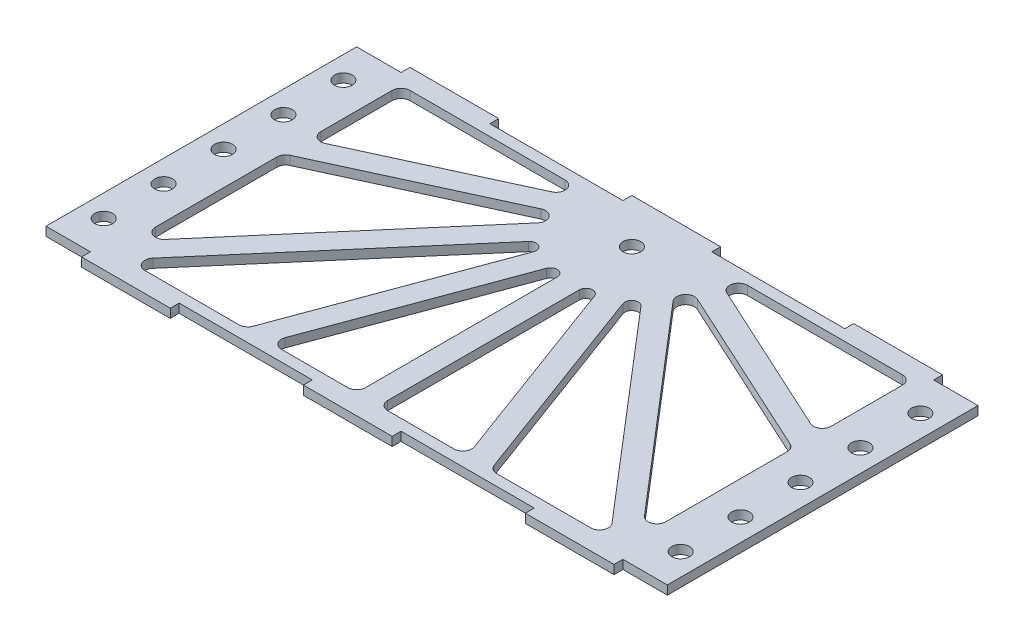
SolidWorks part; units mm, degrees
material "AISI 4340 Steel, normalized"
ref_plane "Front Plane" through (0, 0, 0) normal (0, 0, 1) x (1, 0, 0)
ref_plane "Top Plane" through (0, 0, 0) normal (0, 1, 0) x (1, 0, 0)
ref_plane "Right Plane" through (0, 0, 0) normal (1, 0, 0) x (0, 0, -1)
sketch "Sketch1" plane through (0, 0, 0) normal (0, 1, 0) x (1, 0, 0)
  line B0 (-34.9462, -16.0725) -> (34.9462, 16.0725)
  line B1 (-65.6176, 32.7066) -> (-65.6176, -115.2934)
  line B2 (-65.6176, -115.2934) -> (214.3824, -115.2934)
  line B3 (214.3824, -115.2934) -> (214.3824, 32.7066)
  line B4 (-40.6176, 19.7066) -> (-40.6176, -12.4384)
  line B5 (33.2748, 23.7066) -> (-36.6176, 23.7066)
  line B6 (-40.6176, -32.2509) -> (-40.6176, -86.9641)
  line B7 (39.1267, 6.9883) -> (-38.289, -28.6169)
  line B8 (-33.5806, -89.5673) -> (43.8351, 0.751)
  line B9 (-26.0496, -106.2934) -> (16.328, -106.2934)
  line B10 (20.0796, -103.6812) -> (54.1909, -11.4664)
  line B11 (49.0994, -8.4732) -> (-29.0866, -99.6903)
  line B12 (35.52, -106.2934) -> (65.3824, -106.2934)
  line B13 (63.5687, -14.9385) -> (31.7685, -100.9057)
  line B14 (69.3824, -102.2934) -> (69.3824, -15.9793)
  line B15 (83.3824, -106.2934) -> (113.2448, -106.2934)
  line B16 (79.3824, -15.9793) -> (79.3824, -102.2934)
  line B17 (116.9963, -100.9057) -> (85.1961, -14.9385)
  line B18 (189.3824, -12.4384) -> (189.3824, 19.7066)
  line B19 (113.8186, 16.0725) -> (183.711, -16.0725)
  line B20 (185.3824, 23.7066) -> (115.49, 23.7066)
  line B21 (187.0538, -28.6169) -> (109.6381, 6.9883)
  line B22 (189.3824, -86.9641) -> (189.3824, -32.2509)
  line B23 (104.9297, 0.751) -> (182.3454, -89.5673)
  line B24 (132.4368, -106.2934) -> (174.8144, -106.2934)
  line B25 (94.5739, -11.4664) -> (128.6852, -103.6812)
  line B26 (177.8514, -99.6903) -> (99.6654, -8.4732)
  line B27 (-65.6176, 32.7066) -> (214.3824, 32.7066)
  circle B28 centre (74.3824, 12.7066) radius 4
  circle B29 centre (204.3824, 12.7066) radius 4
  circle B30 centre (204.3824, -14.2934) radius 4
  circle B31 centre (204.3824, -41.2934) radius 4
  circle B32 centre (204.3824, -68.2934) radius 4
  circle B33 centre (204.3824, -95.2934) radius 4
  circle B34 centre (-55.6176, -95.2934) radius 4
  circle B35 centre (-55.6176, -68.2934) radius 4
  circle B36 centre (-55.6176, -41.2934) radius 4
  circle B37 centre (-55.6176, -14.2934) radius 4
  circle B38 centre (-55.6176, 12.7066) radius 4
  arc B39 (34.9462, 16.0725) -> (33.2748, 23.7066) centre (33.2748, 19.7066) ccw
  arc B40 (-40.6176, -12.4384) -> (-34.9462, -16.0725) centre (-36.6176, -12.4384) ccw
  arc B41 (-36.6176, 23.7066) -> (-40.6176, 19.7066) centre (-36.6176, 19.7066) ccw
  arc B42 (-40.6176, -86.9641) -> (-33.5806, -89.5673) centre (-36.6176, -86.9641) ccw
  arc B43 (43.8351, 0.751) -> (39.1267, 6.9883) centre (40.7981, 3.3542) ccw
  arc B44 (-29.0866, -99.6903) -> (-26.0496, -106.2934) centre (-26.0496, -102.2934) ccw
  arc B45 (16.328, -106.2934) -> (20.0796, -103.6812) centre (16.328, -102.2934) ccw
  arc B46 (54.1909, -11.4664) -> (49.0994, -8.4732) centre (51.3772, -10.4256) ccw
  arc B47 (65.3824, -106.2934) -> (69.3824, -102.2934) centre (65.3824, -102.2934) ccw
  arc B48 (31.7685, -100.9057) -> (35.52, -106.2934) centre (35.52, -102.2934) ccw
  arc B49 (69.3824, -15.9793) -> (63.5687, -14.9385) centre (66.3824, -15.9793) ccw
  arc B50 (113.2448, -106.2934) -> (116.9963, -100.9057) centre (113.2448, -102.2934) ccw
  arc B51 (79.3824, -102.2934) -> (83.3824, -106.2934) centre (83.3824, -102.2934) ccw
  arc B52 (85.1961, -14.9385) -> (79.3824, -15.9793) centre (82.3824, -15.9793) ccw
  arc B53 (183.711, -16.0725) -> (189.3824, -12.4384) centre (185.3824, -12.4384) ccw
  arc B54 (189.3824, 19.7066) -> (185.3824, 23.7066) centre (185.3824, 19.7066) ccw
  arc B55 (115.49, 23.7066) -> (113.8186, 16.0725) centre (115.49, 19.7066) ccw
  arc B56 (109.6381, 6.9883) -> (104.9297, 0.751) centre (107.9667, 3.3542) ccw
  arc B57 (189.3824, -32.2509) -> (187.0538, -28.6169) centre (185.3824, -32.2509) ccw
  arc B58 (182.3454, -89.5673) -> (189.3824, -86.9641) centre (185.3824, -86.9641) ccw
  arc B59 (174.8144, -106.2934) -> (177.8514, -99.6903) centre (174.8144, -102.2934) ccw
  arc B60 (128.6852, -103.6812) -> (132.4368, -106.2934) centre (132.4368, -102.2934) ccw
  arc B61 (99.6654, -8.4732) -> (94.5739, -11.4664) centre (97.3876, -10.4256) ccw
sketch_block_instance "Block-pedalbox bottom-1"
sketch_block "Block-pedalbox bottom"
sketch "Sketch2" plane through (0, 0, 0) normal (0, 1, 0) x (1, 0, 0)
  line L0 (39.1267, 6.9883) -> (-38.289, -28.6169) construction
  line L1 (-33.5806, -89.5673) -> (43.8351, 0.751) construction
  line L2 (-40.6176, -32.2509) -> (-40.6176, -86.9641) construction
  line L3 (-65.6176, 32.7066) -> (-65.6176, -115.2934) construction
  line L4 (-65.6176, -115.2934) -> (214.3824, -115.2934) construction
  line L5 (214.3824, -115.2934) -> (214.3824, 32.7066) construction
  line L6 (-65.6176, 32.7066) -> (214.3824, 32.7066) construction
  line L7 (-40.6176, 19.7066) -> (-40.6176, -12.4384) construction
  line L8 (-34.9462, -16.0725) -> (34.9462, 16.0725) construction
  line L9 (33.2748, 23.7066) -> (-36.6176, 23.7066) construction
  line L10 (-26.0496, -106.2934) -> (16.328, -106.2934) construction
  line L11 (49.0994, -8.4732) -> (-29.0866, -99.6903) construction
  line L12 (20.0796, -103.6812) -> (54.1909, -11.4664) construction
  line L13 (79.3824, -15.9793) -> (79.3824, -102.2934) construction
  line L14 (83.3824, -106.2934) -> (113.2448, -106.2934) construction
  line L15 (116.9963, -100.9057) -> (85.1961, -14.9385) construction
  line L16 (35.52, -106.2934) -> (65.3824, -106.2934) construction
  line L17 (69.3824, -102.2934) -> (69.3824, -15.9793) construction
  line L18 (63.5687, -14.9385) -> (31.7685, -100.9057) construction
  line L19 (187.0538, -28.6169) -> (109.6381, 6.9883) construction
  line L20 (104.9297, 0.751) -> (182.3454, -89.5673) construction
  line L21 (189.3824, -86.9641) -> (189.3824, -32.2509) construction
  line L22 (185.3824, 23.7066) -> (115.49, 23.7066) construction
  line L23 (189.3824, -12.4384) -> (189.3824, 19.7066) construction
  line L24 (113.8186, 16.0725) -> (183.711, -16.0725) construction
  line L25 (94.5739, -11.4664) -> (128.6852, -103.6812) construction
  line L26 (132.4368, -106.2934) -> (174.8144, -106.2934) construction
  line L27 (177.8514, -99.6903) -> (99.6654, -8.4732) construction
  line L28 (39.1267, 6.9883) -> (-38.289, -28.6169)
  line L29 (-33.5806, -89.5673) -> (43.8351, 0.751)
  line L30 (-40.6176, -32.2509) -> (-40.6176, -86.9641)
  line L31 (-65.6176, 28.7066) -> (-65.6176, -111.2934)
  line L32 (-45.6176, -115.2934) -> (-5.6176, -115.2934)
  line L33 (214.3824, -111.2934) -> (214.3824, 28.7066)
  line L34 (-45.6176, 32.7066) -> (-5.6176, 32.7066)
  line L35 (-40.6176, 19.7066) -> (-40.6176, -12.4384)
  line L36 (-34.9462, -16.0725) -> (34.9462, 16.0725)
  line L37 (33.2748, 23.7066) -> (-36.6176, 23.7066)
  line L38 (-26.0496, -106.2934) -> (16.328, -106.2934)
  line L39 (49.0994, -8.4732) -> (-29.0866, -99.6903)
  line L40 (20.0796, -103.6812) -> (54.1909, -11.4664)
  line L41 (79.3824, -15.9793) -> (79.3824, -102.2934)
  line L42 (83.3824, -106.2934) -> (113.2448, -106.2934)
  line L43 (116.9963, -100.9057) -> (85.1961, -14.9385)
  line L44 (35.52, -106.2934) -> (65.3824, -106.2934)
  line L45 (69.3824, -102.2934) -> (69.3824, -15.9793)
  line L46 (63.5687, -14.9385) -> (31.7685, -100.9057)
  line L47 (187.0538, -28.6169) -> (109.6381, 6.9883)
  line L48 (104.9297, 0.751) -> (182.3454, -89.5673)
  line L49 (189.3824, -86.9641) -> (189.3824, -32.2509)
  line L50 (185.3824, 23.7066) -> (115.49, 23.7066)
  line L51 (189.3824, -12.4384) -> (189.3824, 19.7066)
  line L52 (113.8186, 16.0725) -> (183.711, -16.0725)
  line L53 (94.5739, -11.4664) -> (128.6852, -103.6812)
  line L54 (132.4368, -106.2934) -> (174.8144, -106.2934)
  line L55 (177.8514, -99.6903) -> (99.6654, -8.4732)
  line L56 (74.3824, 28.7066) -> (74.3824, -115.2934) construction
  line L57 (-65.6176, 28.7066) -> (-45.6176, 28.7066)
  line L58 (54.3824, 28.7066) -> (54.3824, 32.7066)
  line L59 (-5.6176, 28.7066) -> (-5.6176, 32.7066)
  line L60 (-45.6176, 28.7066) -> (-45.6176, 32.7066)
  line L61 (94.3824, 28.7066) -> (94.3824, 32.7066)
  line L62 (154.3824, 28.7066) -> (154.3824, 32.7066)
  line L63 (194.3824, 28.7066) -> (194.3824, 32.7066)
  line L64 (-65.6176, -41.2934) -> (74.3824, -41.2934) construction
  line L65 (194.3824, -111.2934) -> (194.3824, -115.2934)
  line L66 (154.3824, -111.2934) -> (154.3824, -115.2934)
  line L67 (94.3824, -111.2934) -> (94.3824, -115.2934)
  line L68 (54.3824, -111.2934) -> (54.3824, -115.2934)
  line L69 (-5.6176, -111.2934) -> (-5.6176, -115.2934)
  line L70 (-65.6176, -111.2934) -> (-45.6176, -111.2934)
  line L71 (-45.6176, -111.2934) -> (-45.6176, -115.2934)
  line L72 (54.3824, 32.7066) -> (94.3824, 32.7066)
  line L73 (154.3824, 32.7066) -> (194.3824, 32.7066)
  line L74 (-5.6176, 28.7066) -> (54.3824, 28.7066)
  line L75 (94.3824, 28.7066) -> (154.3824, 28.7066)
  line L76 (194.3824, 28.7066) -> (214.3824, 28.7066)
  line L77 (-5.6176, -111.2934) -> (54.3824, -111.2934)
  line L78 (54.3824, -115.2934) -> (94.3824, -115.2934)
  line L79 (94.3824, -111.2934) -> (154.3824, -111.2934)
  line L80 (154.3824, -115.2934) -> (194.3824, -115.2934)
  line L81 (194.3824, -111.2934) -> (214.3824, -111.2934)
  arc A0 (43.8351, 0.751) -> (39.1267, 6.9883) centre (40.7981, 3.3542) ccw construction
  arc A1 (-40.6176, -86.9641) -> (-33.5806, -89.5673) centre (-36.6176, -86.9641) ccw construction
  circle A2 centre (-55.6176, 12.7066) radius 4 construction
  circle A3 centre (-55.6176, -14.2934) radius 4 construction
  circle A4 centre (-55.6176, -41.2934) radius 4 construction
  circle A5 centre (-55.6176, -68.2934) radius 4 construction
  circle A6 centre (-55.6176, -95.2934) radius 4 construction
  circle A7 centre (204.3824, -95.2934) radius 4 construction
  circle A8 centre (204.3824, -68.2934) radius 4 construction
  circle A9 centre (204.3824, -41.2934) radius 4 construction
  circle A10 centre (204.3824, -14.2934) radius 4 construction
  circle A11 centre (204.3824, 12.7066) radius 4 construction
  circle A12 centre (74.3824, 12.7066) radius 4 construction
  arc A13 (-40.6176, -12.4384) -> (-34.9462, -16.0725) centre (-36.6176, -12.4384) ccw construction
  arc A14 (34.9462, 16.0725) -> (33.2748, 23.7066) centre (33.2748, 19.7066) ccw construction
  arc A15 (-36.6176, 23.7066) -> (-40.6176, 19.7066) centre (-36.6176, 19.7066) ccw construction
  arc A16 (-29.0866, -99.6903) -> (-26.0496, -106.2934) centre (-26.0496, -102.2934) ccw construction
  arc A17 (54.1909, -11.4664) -> (49.0994, -8.4732) centre (51.3772, -10.4256) ccw construction
  arc A18 (16.328, -106.2934) -> (20.0796, -103.6812) centre (16.328, -102.2934) ccw construction
  arc A19 (79.3824, -102.2934) -> (83.3824, -106.2934) centre (83.3824, -102.2934) ccw construction
  arc A20 (113.2448, -106.2934) -> (116.9963, -100.9057) centre (113.2448, -102.2934) ccw construction
  arc A21 (85.1961, -14.9385) -> (79.3824, -15.9793) centre (82.3824, -15.9793) ccw construction
  arc A22 (65.3824, -106.2934) -> (69.3824, -102.2934) centre (65.3824, -102.2934) ccw construction
  arc A23 (69.3824, -15.9793) -> (63.5687, -14.9385) centre (66.3824, -15.9793) ccw construction
  arc A24 (31.7685, -100.9057) -> (35.52, -106.2934) centre (35.52, -102.2934) ccw construction
  arc A25 (109.6381, 6.9883) -> (104.9297, 0.751) centre (107.9667, 3.3542) ccw construction
  arc A26 (182.3454, -89.5673) -> (189.3824, -86.9641) centre (185.3824, -86.9641) ccw construction
  arc A27 (189.3824, -32.2509) -> (187.0538, -28.6169) centre (185.3824, -32.2509) ccw construction
  arc A28 (189.3824, 19.7066) -> (185.3824, 23.7066) centre (185.3824, 19.7066) ccw construction
  arc A29 (183.711, -16.0725) -> (189.3824, -12.4384) centre (185.3824, -12.4384) ccw construction
  arc A30 (115.49, 23.7066) -> (113.8186, 16.0725) centre (115.49, 19.7066) ccw construction
  arc A31 (128.6852, -103.6812) -> (132.4368, -106.2934) centre (132.4368, -102.2934) ccw construction
  arc A32 (174.8144, -106.2934) -> (177.8514, -99.6903) centre (174.8144, -102.2934) ccw construction
  arc A33 (99.6654, -8.4732) -> (94.5739, -11.4664) centre (97.3876, -10.4256) ccw construction
  arc A34 (43.8351, 0.751) -> (39.1267, 6.9883) centre (40.7981, 3.3542) ccw
  arc A35 (-40.6176, -86.9641) -> (-33.5806, -89.5673) centre (-36.6176, -86.9641) ccw
  circle A36 centre (-55.6176, 12.7066) radius 4
  circle A37 centre (-55.6176, -14.2934) radius 4
  circle A38 centre (-55.6176, -41.2934) radius 4
  circle A39 centre (-55.6176, -68.2934) radius 4
  circle A40 centre (-55.6176, -95.2934) radius 4
  circle A41 centre (204.3824, -95.2934) radius 4
  circle A42 centre (204.3824, -68.2934) radius 4
  circle A43 centre (204.3824, -41.2934) radius 4
  circle A44 centre (204.3824, -14.2934) radius 4
  circle A45 centre (204.3824, 12.7066) radius 4
  circle A46 centre (74.3824, 12.7066) radius 4
  arc A47 (-40.6176, -12.4384) -> (-34.9462, -16.0725) centre (-36.6176, -12.4384) ccw
  arc A48 (34.9462, 16.0725) -> (33.2748, 23.7066) centre (33.2748, 19.7066) ccw
  arc A49 (-36.6176, 23.7066) -> (-40.6176, 19.7066) centre (-36.6176, 19.7066) ccw
  arc A50 (-29.0866, -99.6903) -> (-26.0496, -106.2934) centre (-26.0496, -102.2934) ccw
  arc A51 (54.1909, -11.4664) -> (49.0994, -8.4732) centre (51.3772, -10.4256) ccw
  arc A52 (16.328, -106.2934) -> (20.0796, -103.6812) centre (16.328, -102.2934) ccw
  arc A53 (79.3824, -102.2934) -> (83.3824, -106.2934) centre (83.3824, -102.2934) ccw
  arc A54 (113.2448, -106.2934) -> (116.9963, -100.9057) centre (113.2448, -102.2934) ccw
  arc A55 (85.1961, -14.9385) -> (79.3824, -15.9793) centre (82.3824, -15.9793) ccw
  arc A56 (65.3824, -106.2934) -> (69.3824, -102.2934) centre (65.3824, -102.2934) ccw
  arc A57 (69.3824, -15.9793) -> (63.5687, -14.9385) centre (66.3824, -15.9793) ccw
  arc A58 (31.7685, -100.9057) -> (35.52, -106.2934) centre (35.52, -102.2934) ccw
  arc A59 (109.6381, 6.9883) -> (104.9297, 0.751) centre (107.9667, 3.3542) ccw
  arc A60 (182.3454, -89.5673) -> (189.3824, -86.9641) centre (185.3824, -86.9641) ccw
  arc A61 (189.3824, -32.2509) -> (187.0538, -28.6169) centre (185.3824, -32.2509) ccw
  arc A62 (189.3824, 19.7066) -> (185.3824, 23.7066) centre (185.3824, 19.7066) ccw
  arc A63 (183.711, -16.0725) -> (189.3824, -12.4384) centre (185.3824, -12.4384) ccw
  arc A64 (115.49, 23.7066) -> (113.8186, 16.0725) centre (115.49, 19.7066) ccw
  arc A65 (128.6852, -103.6812) -> (132.4368, -106.2934) centre (132.4368, -102.2934) ccw
  arc A66 (174.8144, -106.2934) -> (177.8514, -99.6903) centre (174.8144, -102.2934) ccw
  arc A67 (99.6654, -8.4732) -> (94.5739, -11.4664) centre (97.3876, -10.4256) ccw
  arc A68 (-40.6176, -32.2509) -> (-38.289, -28.6169) centre (-36.6176, -32.2509) cw
  dimension "D1" = 4
  dimension "D2" = 20
  dimension "D3" = 60
  dimension "D4" = 40
extrude "Boss-Extrude1" add sketch "Sketch2" along normal blind 4
